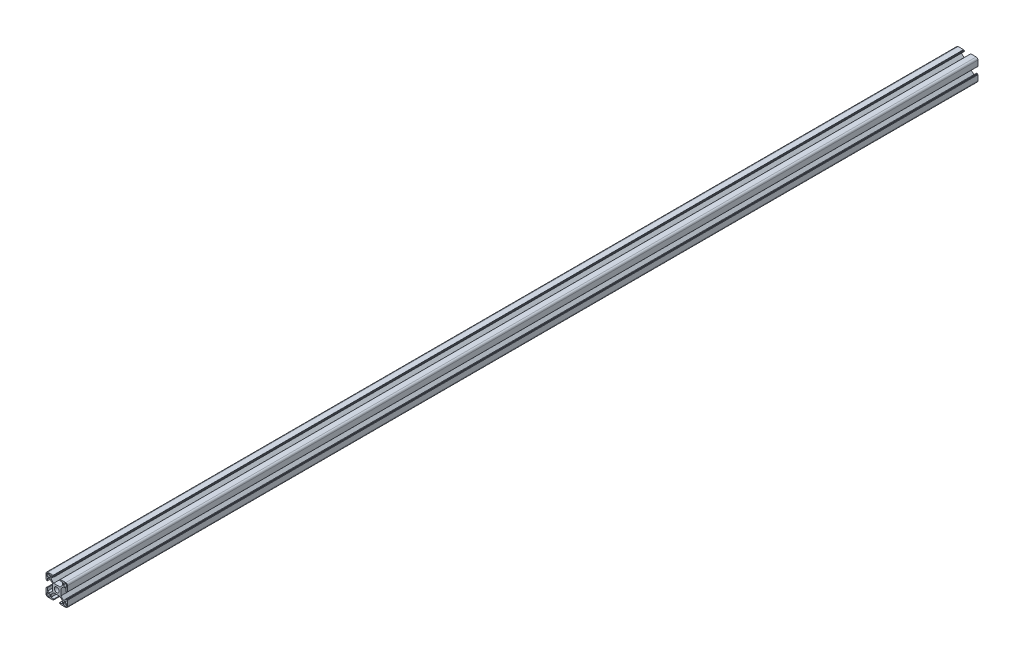
SolidWorks part; units mm, degrees
material "6061-T6 (SS)"
ref_plane "前视基准面" through (0, 0, 0) normal (0, 0, 1) x (1, 0, 0)
ref_plane "上视基准面" through (0, 0, 0) normal (0, 1, 0) x (1, 0, 0)
ref_plane "右视基准面" through (0, 0, 0) normal (1, 0, 0) x (0, 0, -1)
sketch "Sketch1" plane through (0, 0, 0) normal (0, 0, 1) x (1, 0, 0)
  line L0 (-5.1, 15) -> (-5.1, 14.2)
  line L1 (-12.5, -15) -> (12.5, -15)
  line L2 (-15, -12.5) -> (-15, 12.5)
  line L3 (-12.5, 15) -> (12.5, 15)
  line L4 (15, -12.5) -> (15, 12.5)
  line L5 (-15, -15) -> (15, 15) construction
  line L6 (-15, 15) -> (15, -15) construction
  line L7 (-5.1, 14.2) -> (-4.1, 14.2)
  line L8 (-4.1, 14.2) -> (-4.1, 13.2)
  line L9 (-4.1, 13.2) -> (-8.25, 13.2)
  line L10 (-8.25, 13.2) -> (-8.25, 9.5228)
  line L11 (-8.25, 9.5228) -> (-4.4272, 5.7)
  line L12 (-4.4272, 5.7) -> (4.4272, 5.7)
  line L13 (-5.1, 15) -> (5.1, 15)
  line L14 (0, 15) -> (0, 5.7) construction
  line L15 (8.25, 9.5228) -> (4.4272, 5.7)
  line L16 (8.25, 13.2) -> (8.25, 9.5228)
  line L17 (4.1, 13.2) -> (8.25, 13.2)
  line L18 (4.1, 14.2) -> (4.1, 13.2)
  line L19 (5.1, 14.2) -> (4.1, 14.2)
  line L20 (5.1, 15) -> (5.1, 14.2)
  line L21 (15, 5.1) -> (14.2, 5.1)
  line L22 (14.2, 5.1) -> (14.2, 4.1)
  line L23 (14.2, 4.1) -> (13.2, 4.1)
  line L24 (13.2, 4.1) -> (13.2, 8.25)
  line L25 (13.2, 8.25) -> (9.5228, 8.25)
  line L26 (9.5228, 8.25) -> (5.7, 4.4272)
  line L27 (5.7, 4.4272) -> (5.7, -4.4272)
  line L28 (15, 5.1) -> (15, -5.1)
  line L29 (9.5228, -8.25) -> (5.7, -4.4272)
  line L30 (13.2, -8.25) -> (9.5228, -8.25)
  line L31 (13.2, -4.1) -> (13.2, -8.25)
  line L32 (14.2, -4.1) -> (13.2, -4.1)
  line L33 (14.2, -5.1) -> (14.2, -4.1)
  line L34 (15, -5.1) -> (14.2, -5.1)
  line L35 (15, 0) -> (5.7, 0) construction
  line L36 (5.1, -15) -> (5.1, -14.2)
  line L37 (5.1, -14.2) -> (4.1, -14.2)
  line L38 (4.1, -14.2) -> (4.1, -13.2)
  line L39 (4.1, -13.2) -> (8.25, -13.2)
  line L40 (8.25, -13.2) -> (8.25, -9.5228)
  line L41 (8.25, -9.5228) -> (4.4272, -5.7)
  line L42 (4.4272, -5.7) -> (-4.4272, -5.7)
  line L43 (5.1, -15) -> (-5.1, -15)
  line L44 (-8.25, -9.5228) -> (-4.4272, -5.7)
  line L45 (-8.25, -13.2) -> (-8.25, -9.5228)
  line L46 (-4.1, -13.2) -> (-8.25, -13.2)
  line L47 (-4.1, -14.2) -> (-4.1, -13.2)
  line L48 (-5.1, -14.2) -> (-4.1, -14.2)
  line L49 (-5.1, -15) -> (-5.1, -14.2)
  line L50 (0, -15) -> (0, -5.7) construction
  line L51 (-15, -5.1) -> (-14.2, -5.1)
  line L52 (-14.2, -5.1) -> (-14.2, -4.1)
  line L53 (-14.2, -4.1) -> (-13.2, -4.1)
  line L54 (-13.2, -4.1) -> (-13.2, -8.25)
  line L55 (-13.2, -8.25) -> (-9.5228, -8.25)
  line L56 (-9.5228, -8.25) -> (-5.7, -4.4272)
  line L57 (-5.7, -4.4272) -> (-5.7, 4.4272)
  line L58 (-15, -5.1) -> (-15, 5.1)
  line L59 (-9.5228, 8.25) -> (-5.7, 4.4272)
  line L60 (-13.2, 8.25) -> (-9.5228, 8.25)
  line L61 (-13.2, 4.1) -> (-13.2, 8.25)
  line L62 (-14.2, 4.1) -> (-13.2, 4.1)
  line L63 (-14.2, 5.1) -> (-14.2, 4.1)
  line L64 (-15, 5.1) -> (-14.2, 5.1)
  line L65 (-15, 0) -> (-5.7, 0) construction
  line L66 (0, 0) -> (0, 5.7) construction
  circle A0 centre (0, 0) radius 3.4
  arc A1 (-12.5, -15) -> (-15, -12.5) centre (-12.5, -12.5) cw
  arc A2 (12.5, -15) -> (15, -12.5) centre (12.5, -12.5) ccw
  arc A3 (12.5, 15) -> (15, 12.5) centre (12.5, 12.5) cw
  arc A4 (-15, 12.5) -> (-12.5, 15) centre (-12.5, 12.5) cw
  point P0 (0, 0)
  dimension "D3" = 6.8
  dimension "D12" = 2.5
  dimension "D1" = 30
  dimension "D2" = 30
  dimension "D4" = 16.5
  dimension "D5" = 8.2
  dimension "D6" = 10.2
  dimension "D7" = 7.5
  dimension "D9" = 1.8
  dimension "D10" = 1.8
  dimension "D11" = 0.8
  dimension "D8" = 4
extrude "Extrude1" add sketch "Sketch1" along normal blind 1268 contours A4 L2 L64 L63 L62 L61 L60 L59 L57 L56 L55 L54 L53 L52 L51 A1 L1 L49 L48 L47 L46 L45 L44 L42 L41 L40 L39 L38 L37 L36 A2 L4 L34 L33 L32 L31 L30 L29 L27 L26 L25 L24 L23 L22 L21 A3 L3 L20
sketch "Sketch2" plane through (0, 0, 1268) normal (0, 0, 1) x (1, 0, 0)
  line L0 (13.7, 12.7) -> (13.7, 10.55)
  line L1 (-12.7, 13.7) -> (-10.55, 13.7)
  line L2 (-13.7, 12.7) -> (-13.7, 10.55)
  line L3 (-12.7, 9.55) -> (-10.55, 9.55)
  line L4 (-9.55, 12.7) -> (-9.55, 10.55)
  line L5 (-13.7, 13.7) -> (-9.55, 9.55) construction
  line L6 (-13.7, 9.55) -> (-9.55, 13.7) construction
  line L7 (12.7, 13.7) -> (10.55, 13.7)
  line L8 (9.55, 12.7) -> (9.55, 10.55)
  line L9 (12.7, 9.55) -> (10.55, 9.55)
  line L10 (12.7, -13.7) -> (10.55, -13.7)
  line L11 (13.7, -12.7) -> (13.7, -10.55)
  line L12 (12.7, -9.55) -> (10.55, -9.55)
  line L13 (9.55, -12.7) -> (9.55, -10.55)
  line L14 (-13.7, -12.7) -> (-13.7, -10.55)
  line L15 (-12.7, -13.7) -> (-10.55, -13.7)
  line L16 (-9.55, -12.7) -> (-9.55, -10.55)
  line L17 (-12.7, -9.55) -> (-10.55, -9.55)
  line L18 (0, 0) -> (-9.55, 9.55) construction
  line L19 (-12.5, 15) -> (-5.1, 15) construction
  line L20 (-15, 5.1) -> (-15, 12.5) construction
  line L21 (-13.2, 8.25) -> (-9.5228, 8.25) construction
  line L22 (-8.25, 13.2) -> (-8.25, 9.5228) construction
  arc A0 (-13.7, -12.7) -> (-12.7, -13.7) centre (-12.7, -12.7) ccw
  arc A1 (-10.55, -13.7) -> (-9.55, -12.7) centre (-10.55, -12.7) ccw
  arc A2 (-9.55, -10.55) -> (-10.55, -9.55) centre (-10.55, -10.55) ccw
  arc A3 (-13.7, -10.55) -> (-12.7, -9.55) centre (-12.7, -10.55) cw
  arc A4 (13.7, -10.55) -> (12.7, -9.55) centre (12.7, -10.55) ccw
  arc A5 (12.7, -13.7) -> (13.7, -12.7) centre (12.7, -12.7) ccw
  arc A6 (10.55, -13.7) -> (9.55, -12.7) centre (10.55, -12.7) cw
  arc A7 (10.55, -9.55) -> (9.55, -10.55) centre (10.55, -10.55) ccw
  arc A8 (13.7, 12.7) -> (12.7, 13.7) centre (12.7, 12.7) ccw
  arc A9 (13.7, 10.55) -> (12.7, 9.55) centre (12.7, 10.55) cw
  arc A10 (9.55, 10.55) -> (10.55, 9.55) centre (10.55, 10.55) ccw
  arc A11 (10.55, 13.7) -> (9.55, 12.7) centre (10.55, 12.7) ccw
  arc A12 (-10.55, 13.7) -> (-9.55, 12.7) centre (-10.55, 12.7) cw
  arc A13 (-10.55, 9.55) -> (-9.55, 10.55) centre (-10.55, 10.55) ccw
  arc A14 (-13.7, 10.55) -> (-12.7, 9.55) centre (-12.7, 10.55) ccw
  arc A15 (-12.7, 13.7) -> (-13.7, 12.7) centre (-12.7, 12.7) ccw
  point P0 (-11.625, 11.625)
  dimension "D2" = 1
  dimension "D3" = 1.3
  dimension "D4" = 1.3
  dimension "D5" = 1.3
  dimension "D6" = 1.3
  dimension "D1" = 4
extrude "Extrude2" cut sketch "Sketch2" against normal through all
